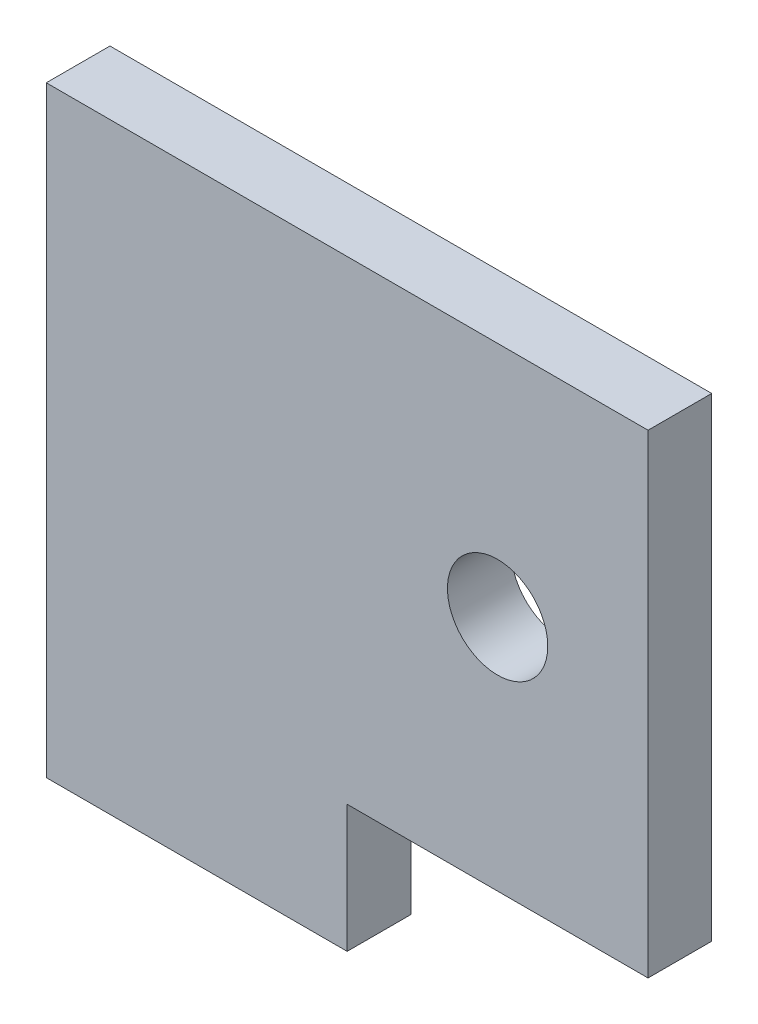
SolidWorks part; units mm, degrees
ref_plane "Front Plane" through (0, 0, 0) normal (0, 0, 1) x (1, 0, 0)
ref_plane "Top Plane" through (0, 0, 0) normal (0, 1, 0) x (1, 0, 0)
ref_plane "Right Plane" through (0, 0, 0) normal (1, 0, 0) x (0, 0, -1)
sketch "Sketch1" plane through (0, 0, 0) normal (0, 0, 1) x (1, 0, 0)
  line L0 (15, 0) -> (15, 6.35)
  line L1 (0, 0) -> (15, 0)
  line L2 (0, 0) -> (0, 30)
  line L3 (0, 30) -> (30, 30)
  line L4 (30, 6.35) -> (30, 30)
  line L5 (15, 6.35) -> (30, 6.35)
  line L6 (22.5, 6.35) -> (22.5, 30) construction
  circle A0 centre (22.5, 18.175) radius 2.5
  dimension "D5" = 5
  dimension "D1" = 30
  dimension "D2" = 30
  dimension "D3" = 6.35
  dimension "D4" = 15
extrude "Boss-Extrude1" add sketch "Sketch1" along normal blind 3.175
